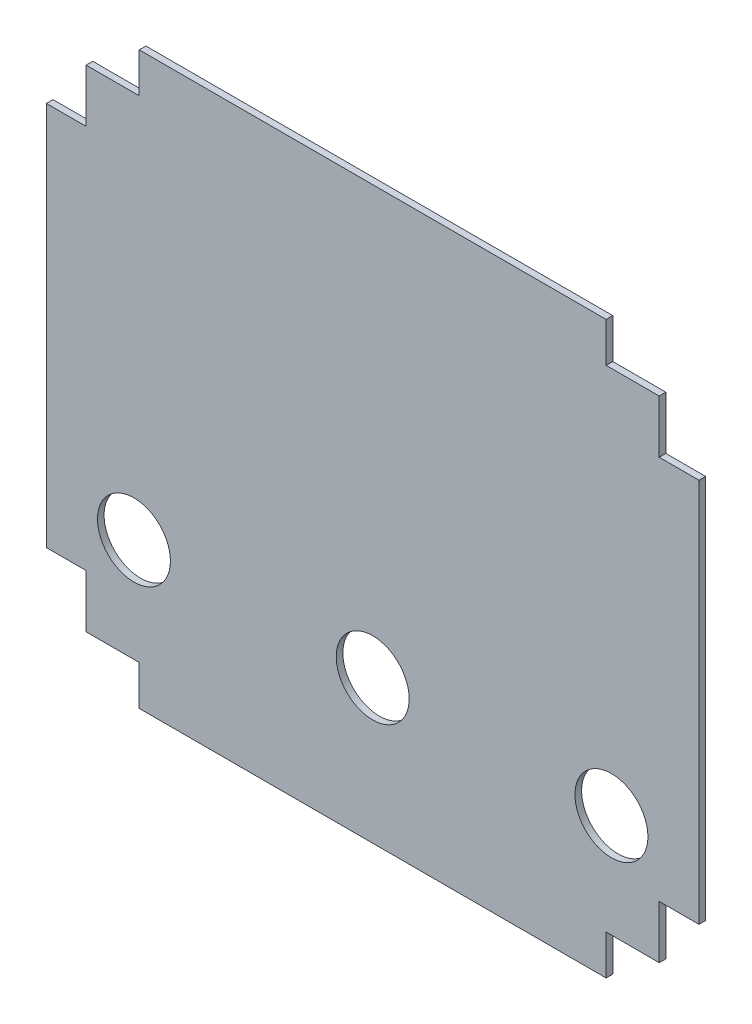
SolidWorks part; units mm, degrees
material "Acrílico (Impacto medio-alto)"
ref_plane "Alzado" through (0, 0, 0) normal (0, 0, 1) x (1, 0, 0)
ref_plane "Planta" through (0, 0, 0) normal (0, 1, 0) x (1, 0, 0)
ref_plane "Vista lateral" through (0, 0, 0) normal (1, 0, 0) x (0, 0, -1)
sketch "Croquis1" plane through (0, 0, 0) normal (0, 0, 1) x (1, 0, 0)
  line L0 (-246, 0) -> (246, 0)
  line L1 (0, 0) -> (0, 215) construction
  line L2 (-246, -145) -> (-246, 145)
  line L3 (-246, 145) -> (-216, 145)
  line L4 (-216, 145) -> (-216, 185)
  line L5 (-216, 185) -> (-176, 185)
  line L6 (-176, 185) -> (-176, 215)
  line L7 (-176, 215) -> (176, 215)
  line L8 (246, -145) -> (246, 145)
  line L9 (246, 145) -> (216, 145)
  line L10 (216, 145) -> (216, 185)
  line L11 (216, 185) -> (176, 185)
  line L12 (176, 185) -> (176, 215)
  line L13 (-246, -145) -> (-216, -145)
  line L14 (-216, -145) -> (-216, -185)
  line L15 (-216, -185) -> (-176, -185)
  line L16 (-176, -185) -> (-176, -215)
  line L17 (-176, -215) -> (176, -215)
  line L18 (176, -185) -> (176, -215)
  line L19 (216, -185) -> (176, -185)
  line L20 (216, -145) -> (216, -185)
  line L21 (246, -145) -> (216, -145)
  point P4 (0, 0)
  dimension "D1" = 492
  dimension "D2" = 145
  dimension "D3" = 216
  dimension "D4" = 176
  dimension "D5" = 30
  dimension "D6" = 40
extrude "Saliente-Extruir1" add sketch "Croquis1" along normal blind 5 contours L1 L0 L8 L9 L10 L11 L12 L7 | L0 L1 L7 L6 L5 L4 L3 L2 | L21 L8 L0 L2 L13 L14 L15 L16 L17 L18 L19 L20
sketch "Croquis2" plane through (0, 0, 5) normal (0, 0, 1) x (1, 0, 0)
  line L0 (-246, -145) -> (-246, 145) construction
  line L1 (-176, -215) -> (176, -215) construction
  circle A0 centre (-180, -107) radius 27.5
  circle A1 centre (0, -107) radius 27.5
  circle A2 centre (180, -107) radius 27.5
  dimension "D1" = 55
  dimension "D2" = 66
  dimension "D3" = 108
  dimension "D4" = 180
  dimension "D5" = 180
extrude "Cortar-Extruir1" cut sketch "Croquis2" against normal blind 10
